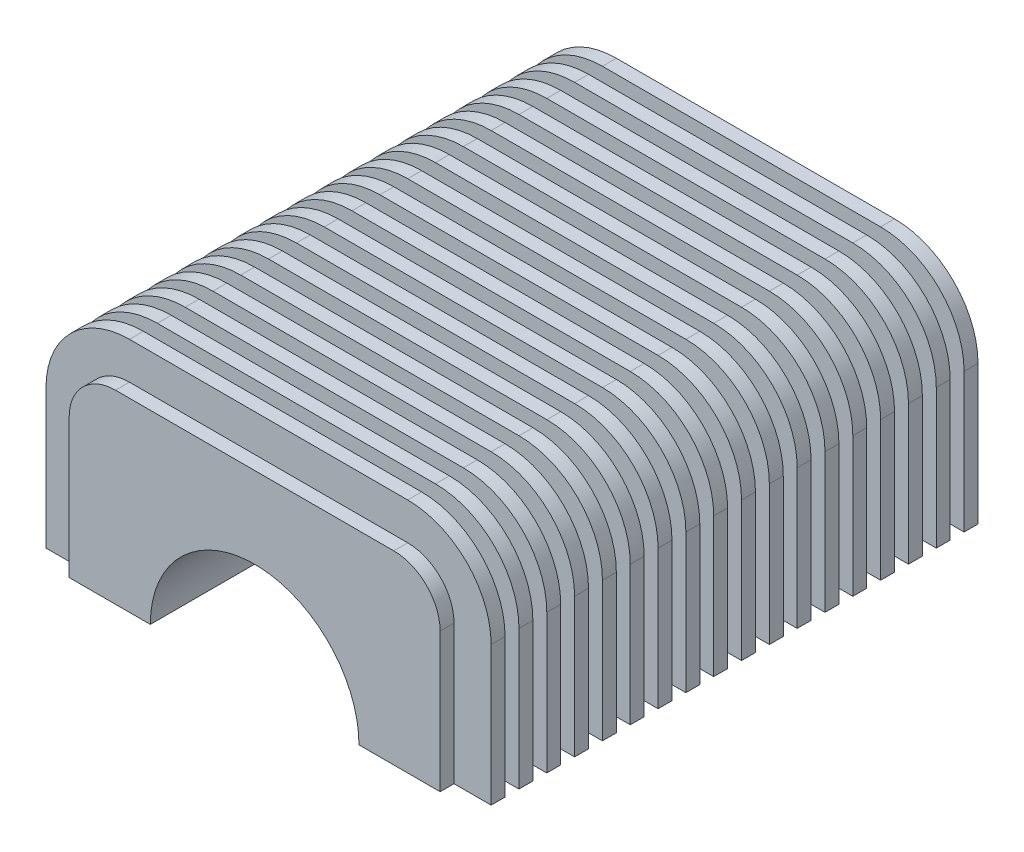
SolidWorks part; units mm, degrees
ref_plane "Płaszczyzna przednia" through (0, 0, 0) normal (0, 0, 1) x (1, 0, 0)
ref_plane "Płaszczyzna górna" through (0, 0, 0) normal (0, 1, 0) x (1, 0, 0)
ref_plane "Płaszczyzna prawa" through (0, 0, 0) normal (1, 0, 0) x (0, 0, -1)
sketch "Szkic1" plane through (0, 0, 0) normal (0, 0, 1) x (1, 0, 0)
  line L1 (-40, 40) -> (40, 40)
  line L2 (-40, 40) -> (-40, 0)
  line L3 (-40, 0) -> (40, 0)
  line L4 (40, 40) -> (40, 0)
  line L5 (-40, 40) -> (40, 0) construction
  line L6 (-40, 0) -> (40, 40) construction
  point P0 (0, 20)
  dimension "D1" = 80
  dimension "D2" = 40
extrude "Dodanie-wyciągnięcie1" add sketch "Szkic1" along normal blind 108
sketch "Szkic2" plane through (0, 0, 0) normal (0, 0, 1) x (1, 0, 0)
  circle A0 centre (0, 0) radius 22.5
  dimension "D1" = 45
extrude "Wytnij-wyciągnięcie3" cut sketch "Szkic2" along normal blind 108 contours A0
fillet "Zaokrąglenie2" radius 10 2 edges at (-40, 40, 54) (40, 40, 54)
sketch "Szkic3" plane through (0, 0, 0) normal (0, 0, 1) x (1, 0, 0)
  line L0 (-40, 30) -> (-40, 0) construction
  line L1 (30, 40) -> (-30, 40) construction
  line L2 (40, 0) -> (40, 30) construction
  line L3 (-40, 30) -> (-40, 0)
  line L4 (30, 40) -> (-30, 40)
  line L5 (40, 0) -> (40, 30)
  line L6 (48, 0) -> (48, 30)
  line L7 (30, 48) -> (-30, 48)
  line L8 (-48, 30) -> (-48, 0)
  line L9 (48, 0) -> (40, 0)
  line L10 (-48, 0) -> (-40, 0)
  arc A0 (-30, 40) -> (-40, 30) centre (-30, 30) ccw construction
  arc A1 (40, 30) -> (30, 40) centre (30, 30) ccw construction
  arc A2 (-30, 40) -> (-40, 30) centre (-30, 30) ccw
  arc A3 (40, 30) -> (30, 40) centre (30, 30) ccw
  arc A4 (48, 30) -> (30, 48) centre (30, 30) ccw
  arc A5 (-30, 48) -> (-48, 30) centre (-30, 30) ccw
  dimension "D1" = 8
extrude "Dodanie-wyciągnięcie2" add sketch "Szkic3" along normal blind 3 contours L10 L3 A2 L4 A3 L5 L9 L6 A4 L7 A5 L8
pattern_linear "Szyk liniowy4" count 18 spacing 6 along (0, 0, 1) of "Dodanie-wyciągnięcie2"
